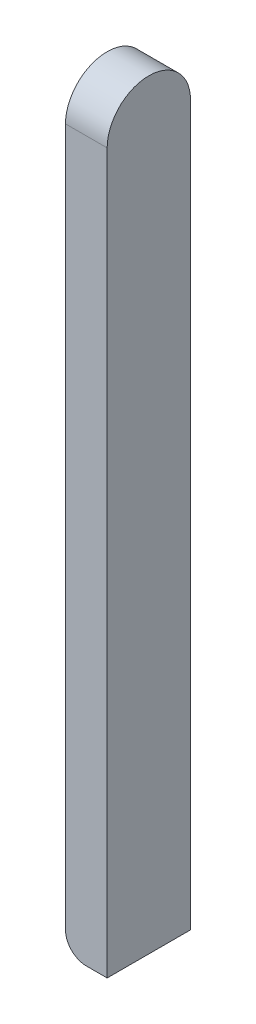
SolidWorks part; units mm, degrees
material "Zinc AC41A Alloy, As Cast"
ref_plane "Front Plane" through (0, 0, 0) normal (0, 0, 1) x (1, 0, 0)
ref_plane "Top Plane" through (0, 0, 0) normal (0, 1, 0) x (1, 0, 0)
ref_plane "Right Plane" through (0, 0, 0) normal (1, 0, 0) x (0, 0, -1)
sketch "Sketch1" plane through (0, 0, 0) normal (1, 0, 0) x (0, 0, -1)
  line L0 (-1, 8.125) -> (-1, -9.125)
  line L1 (-1, -9.125) -> (1, -9.125)
  line L2 (1, 8.125) -> (1, -9.125)
  arc A0 (-1, 8.125) -> (1, 8.125) centre (0, 8.125) cw
  dimension "D1" = 1
  dimension "D2" = 17.25
extrude "Boss-Extrude1" add sketch "Sketch1" along normal blind 1
fillet "Fillet4" radius 0.5 1 edges at (0, -9.125, 0)
